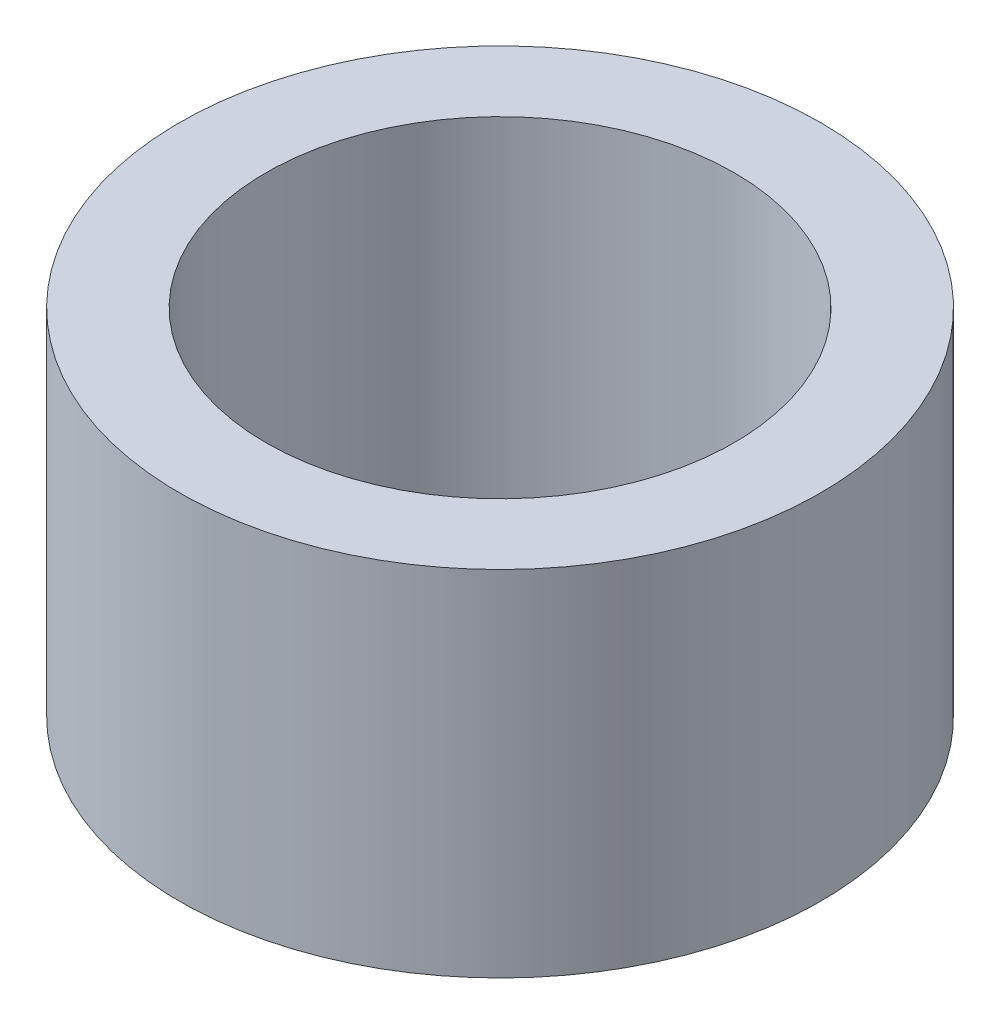
SolidWorks part; units mm, degrees
ref_plane "Front Plane" through (0, 0, 0) normal (0, 0, 1) x (1, 0, 0)
ref_plane "Top Plane" through (0, 0, 0) normal (0, 1, 0) x (1, 0, 0)
ref_plane "Right Plane" through (0, 0, 0) normal (1, 0, 0) x (0, 0, -1)
sketch "Sketch1" plane through (0, 0, 0) normal (0, 1, 0) x (1, 0, 0)
  circle A0 centre (0, 0) radius 4.1326
  circle A1 centre (0, 0) radius 3.0162
  dimension "D1" = 8.2652
  dimension "D2" = 6.0325
extrude "Boss-Extrude1" add sketch "Sketch1" along normal blind 4.5593
equation "\"material_width\" = 0.1795"
equation "\"max32_width\" = 2.1"
equation "\"max32_length\" = 4.0"
equation "\"max32_hole_diameter\" = 0.12"
equation "\"max32_dist2hole_width\" = 0.1"
equation "\"max32_dist2hole1_length\" = 0.6"
equation "\"max32_dist2hole2_length\" = 3.8"
equation "\"head_height\" = 2.0"
equation "\"neck_height\" = \"max32_width\""
equation "\"washer_height\" = 0.1"
equation "\"wall_length\" = 3.5"
equation "\"wall_height\" = 1.5"
equation "\"extra_space\" = 0.25"
equation "\"arc_radius\" = \"wall_length\" + \"washer_height\" + \"neck_height\" + (\"head_height\"/2)"
equation "\"arc_wall_height\" = \"arc_radius\" + \"wall_length\" + \"extra_space\""
equation "\"foot_length\" = 1.0"
equation "\"peg_diameter\" = 0.2475"
equation "\"barring_diameter\" = 0.8657"
equation "\"barring_int_diameter\" = 0.3154"
equation "\"imu_space\" = 0.8"
equation "\"encoder_height\" = 0.8587"
equation "\"encoder_sub_height\" = 0.3827"
equation "\"encoder_length\" = 1.1043"
equation "\"encoder_sub_length\" = 0.5886"
equation "\"encoder_width\" = 0.8669"
equation "\"standoff_small\" = 0.3752"
equation "\"imu_hole_diameter\" = 0.085"
equation "\"D1@Sketch1\"=\"barring_int_diameter\" + 0.01"
equation "\"D2@Sketch1\"=\"peg_diameter\" - 0.01"
equation "\"D1@Boss-Extrude1\"=\"material_width\""
